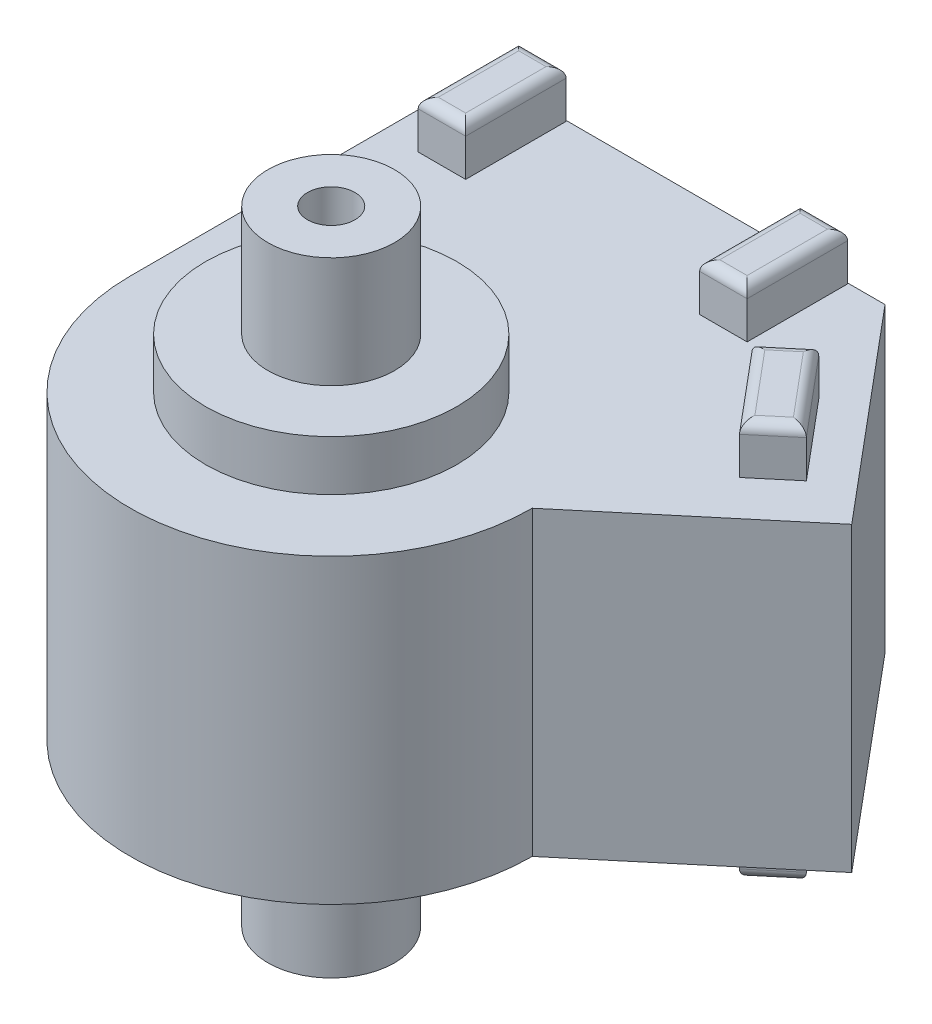
SolidWorks part; units mm, degrees
ref_plane "Front Plane" through (0, 0, 0) normal (0, 0, 1) x (1, 0, 0)
ref_plane "Top Plane" through (0, 0, 0) normal (0, 1, 0) x (1, 0, 0)
ref_plane "Right Plane" through (0, 0, 0) normal (1, 0, 0) x (0, 0, -1)
sketch "Sketch1" plane through (0, 0, 0) normal (0, 0, 1) x (1, 0, 0)
  line L0 (-12.7, -9.525) -> (-12.7, 9.525)
  line L1 (-12.7, 9.525) -> (-7.9375, 9.525)
  line L2 (-7.9375, 9.525) -> (-7.9375, 12.7)
  line L3 (-7.9375, 12.7) -> (-4, 12.7)
  line L4 (-4, 12.7) -> (-4, 19.7)
  line L5 (0, 0) -> (0, 19.7) construction
  line L6 (0, 19.7) -> (-4, 19.7)
  line L7 (0, 0) -> (-12.7, 0) construction
  line L8 (-4, 19.7) -> (4, 19.7) construction
  line L9 (-7.9375, 12.7) -> (7.9375, 12.7) construction
  line L10 (-12.7, 9.525) -> (12.7, 9.525) construction
  line L11 (-12.7, -9.525) -> (-7.9375, -9.525)
  line L12 (-7.9375, -9.525) -> (-7.9375, -12.7)
  line L13 (-7.9375, -12.7) -> (-4, -12.7)
  line L14 (-4, -12.7) -> (-4, -19.7)
  line L15 (-4, -19.7) -> (0, -19.7)
  line L16 (0, -19.7) -> (0, 19.7)
  point P9 (0, 9.525)
  point P12 (0, 19.7)
  point P14 (0, 12.7)
  dimension "D1" = 19.05
  dimension "D2" = 3.175
  dimension "D3" = 7
  dimension "D4" = 8
  dimension "D5" = 15.875
  dimension "D6" = 25.4
  dimension "D7" = 25.4
revolve "Revolve1" add sketch "Sketch1" angle 360 about L5
sketch "Sketch2" plane through (0, 9.525, 0) normal (0, 1, 0) x (1, 0, 0)
  line L0 (12.7, 0) -> (23.6726, 9.2071)
  line L1 (23.6726, 9.2071) -> (12.7, 22.2837)
  line L3 (12.7, 22.2837) -> (-12.7, 22.2837)
  line L4 (-12.7, 22.2837) -> (-12.7, 0)
  line L5 (-12.7, 0) -> (12.7, 0)
  line L6 (12.7, 0) -> (12.7, 22.2837) construction
  circle A0 centre (0, 0) radius 12.7 construction
  dimension "D1" = 50
  dimension "D2" = 25.4
extrude "Boss-Extrude1" add sketch "Sketch2" against normal up to surface (19.05 mm away) up to face at (7.9375, -9.525, 0)
sketch "Sketch3" plane through (0, 19.7, 0) normal (0, 1, 0) x (1, 0, 0)
  circle A0 centre (0, 0) radius 1.4986
  dimension "D1" = 2.9972
extrude "Cut-Extrude1" cut sketch "Sketch3" against normal through all
sketch "Sketch4" plane through (0, 9.525, 0) normal (0, 1, 0) x (1, 0, 0)
  line L5 (15.7794, 15.0179) -> (13.4834, 13.0913)
  line L6 (13.4834, 13.0913) -> (17.5651, 8.227)
  line L7 (17.5651, 8.227) -> (19.8611, 10.1535)
  line L8 (19.8611, 10.1535) -> (15.7794, 15.0179)
  line L9 (12.7, 0) -> (23.6726, 9.2071) construction
  line L10 (23.6726, 9.2071) -> (12.7, 22.2837) construction
  point P6 (13.3668, 19.0989)
  point P7 (17.4582, 11.1642)
  dimension "D1" = 2.9972
  dimension "D2" = 6.35
  dimension "D3" = 3.175
  dimension "D4" = 2.3114
extrude "Boss-Extrude2" add sketch "Sketch4" along normal blind 2.9972
sketch "Sketch5" plane through (0, 9.525, 0) normal (0, 1, 0) x (1, 0, 0)
  line L0 (-12.7, 22.2837) -> (-12.7, 0) construction
  line L1 (-10.3886, 22.2329) -> (-7.3914, 22.2329)
  line L2 (-10.3886, 22.2329) -> (-10.3886, 15.8829)
  line L3 (-10.3886, 15.8829) -> (-7.3914, 15.8829)
  line L4 (-7.3914, 22.2329) -> (-7.3914, 15.8829)
  line L5 (-10.3886, 22.2329) -> (-7.3914, 15.8829) construction
  line L6 (-10.3886, 15.8829) -> (-7.3914, 22.2329) construction
  line L7 (7.3914, 22.2329) -> (10.3886, 22.2329)
  line L8 (7.3914, 22.2329) -> (7.3914, 15.8829)
  line L9 (7.3914, 15.8829) -> (10.3886, 15.8829)
  line L10 (10.3886, 22.2329) -> (10.3886, 15.8829)
  line L11 (7.3914, 22.2329) -> (10.3886, 15.8829) construction
  line L12 (7.3914, 15.8829) -> (10.3886, 22.2329) construction
  line L13 (12.7, 22.2837) -> (-12.7, 22.2837) construction
  point P0 (-8.89, 19.0579)
  point P5 (8.89, 19.0579)
  dimension "D1" = 2.9972
  dimension "D2" = 2.9972
  dimension "D3" = 6.35
  dimension "D4" = 2.3114
  dimension "D5" = 17.78
  dimension "D6" = 0.0508
extrude "Boss-Extrude3" add sketch "Sketch5" along normal blind 2.9972
fillet "Fillet1" radius 0.635 12 edges at (18.7131, 12.5222, -9.1902) (15.5242, 12.5222, -10.6591) (14.6314, 12.5222, -14.0546) (17.8202, 12.5222, -12.5857) (8.89, 12.5222, -15.8829) (7.3914, 12.5222, -19.0579) (8.89, 12.5222, -22.2329) (10.3886, 12.5222, -19.0579) (-8.89, 12.5222, -15.8829) (-10.3886, 12.5222, -19.0579) (-8.89, 12.5222, -22.2329) (-7.3914, 12.5222, -19.0579)
ref_plane "Plane1" through (0, 0, 0) normal (0, 1, 0) x (1, 0, 0)
mirror "Mirror1" about plane through (0, 0, 0) normal (0, 1, 0) of "Fillet1", "Boss-Extrude3", "Boss-Extrude2"
